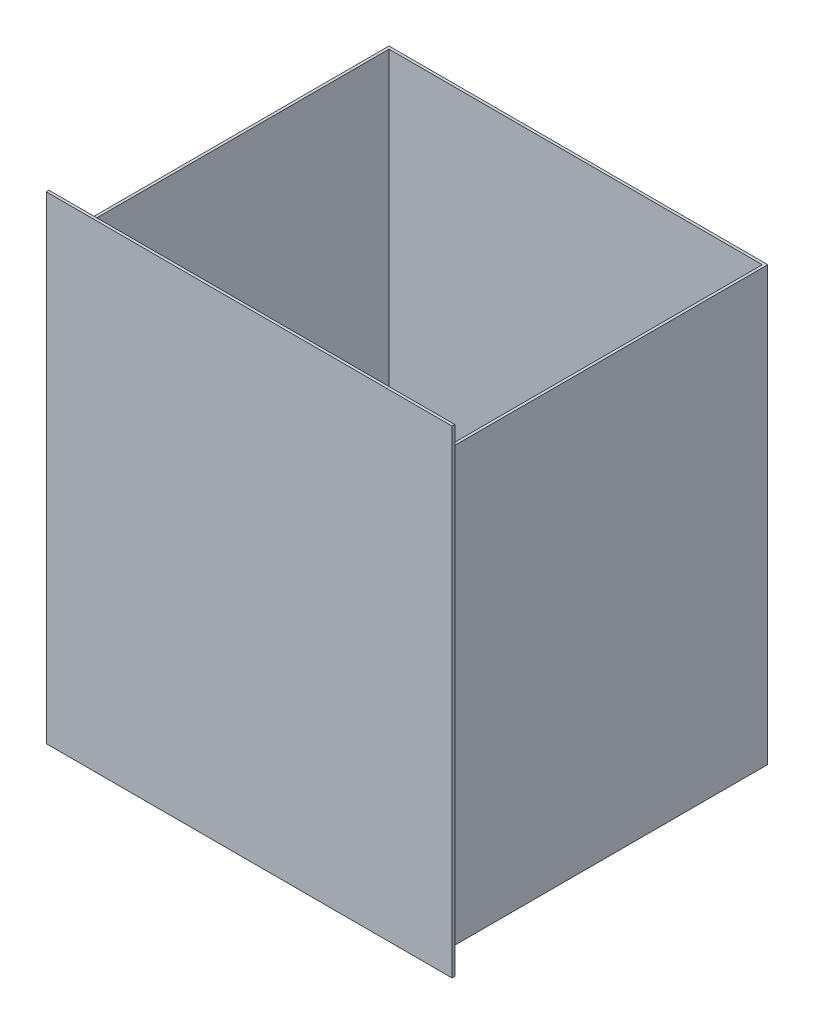
SolidWorks part; units mm, degrees
ref_plane "前视基准面" through (0, 0, 0) normal (0, 0, 1) x (1, 0, 0)
ref_plane "上视基准面" through (0, 0, 0) normal (0, 1, 0) x (1, 0, 0)
ref_plane "右视基准面" through (0, 0, 0) normal (1, 0, 0) x (0, 0, -1)
sketch "草图1" plane through (0, 0, 0) normal (0, 1, 0) x (1, 0, 0)
  line L1 (-210, -180) -> (210, -180)
  line L2 (-210, -180) -> (-210, 180)
  line L3 (-210, 180) -> (210, 180)
  line L4 (210, -180) -> (210, 180)
  line L5 (-210, -180) -> (210, 180) construction
  line L6 (-210, 180) -> (210, -180) construction
  point P0 (0, 0)
  dimension "D1" = 420
  dimension "D2" = 360
extrude "凸台-拉伸1" add sketch "草图1" along normal blind 3
sketch "草图2" plane through (0, 3, 0) normal (0, 1, 0) x (1, 0, 0)
  line L1 (-210, -180) -> (210, -180)
  line L2 (-210, -180) -> (-210, 180)
  line L3 (-210, 180) -> (210, 180)
  line L4 (210, -180) -> (210, 180)
  line L5 (-210, -180) -> (210, 180) construction
  line L6 (-210, 180) -> (210, -180) construction
  point P0 (0, 0)
extrude "拉伸-薄壁1" add sketch "草图2" along normal blind 477 thin thin type one direction reverse wall 3
sketch "草图3" plane through (0, 0, 180) normal (0, 0, 1) x (1, 0, 0)
  line L0 (-210, 480) -> (-210, 0) construction
  line L1 (-230, -20) -> (220, -20)
  line L2 (-230, -20) -> (-230, 510)
  line L3 (-230, 510) -> (220, 510)
  line L4 (220, -20) -> (220, 510)
  line L5 (-210, 480) -> (210, 480) construction
  line L6 (210, 480) -> (210, 0) construction
  line L7 (-210, 0) -> (210, 0) construction
  point P6 (-210, 240)
  dimension "D1" = 20
  dimension "D2" = 30
  dimension "D3" = 10
  dimension "D4" = 20
extrude "凸台-拉伸2" add sketch "草图3" against normal blind 3
